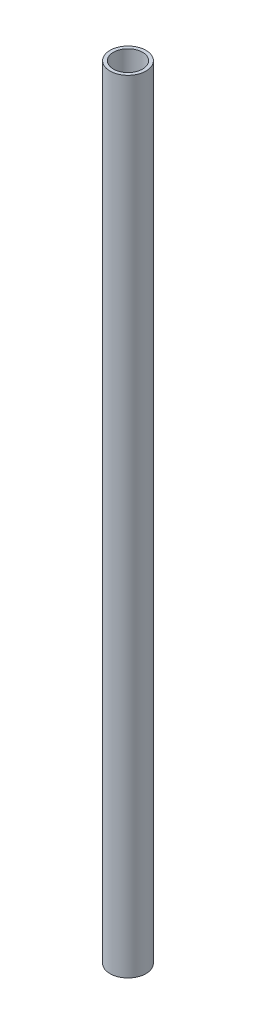
SolidWorks part; units mm, degrees
ref_plane "Front Plane" through (0, 0, 0) normal (0, 0, 1) x (1, 0, 0)
ref_plane "Top Plane" through (0, 0, 0) normal (0, 1, 0) x (1, 0, 0)
ref_plane "Right Plane" through (0, 0, 0) normal (1, 0, 0) x (0, 0, -1)
sketch "Sketch1" plane through (0, 0, 0) normal (0, 1, 0) x (1, 0, 0)
  circle A0 centre (0, 0) radius 6.5
  circle A1 centre (0, 0) radius 8
  dimension "D1" = 13
  dimension "D2" = 16
extrude "Boss-Extrude1" add sketch "Sketch1" along normal blind 348
